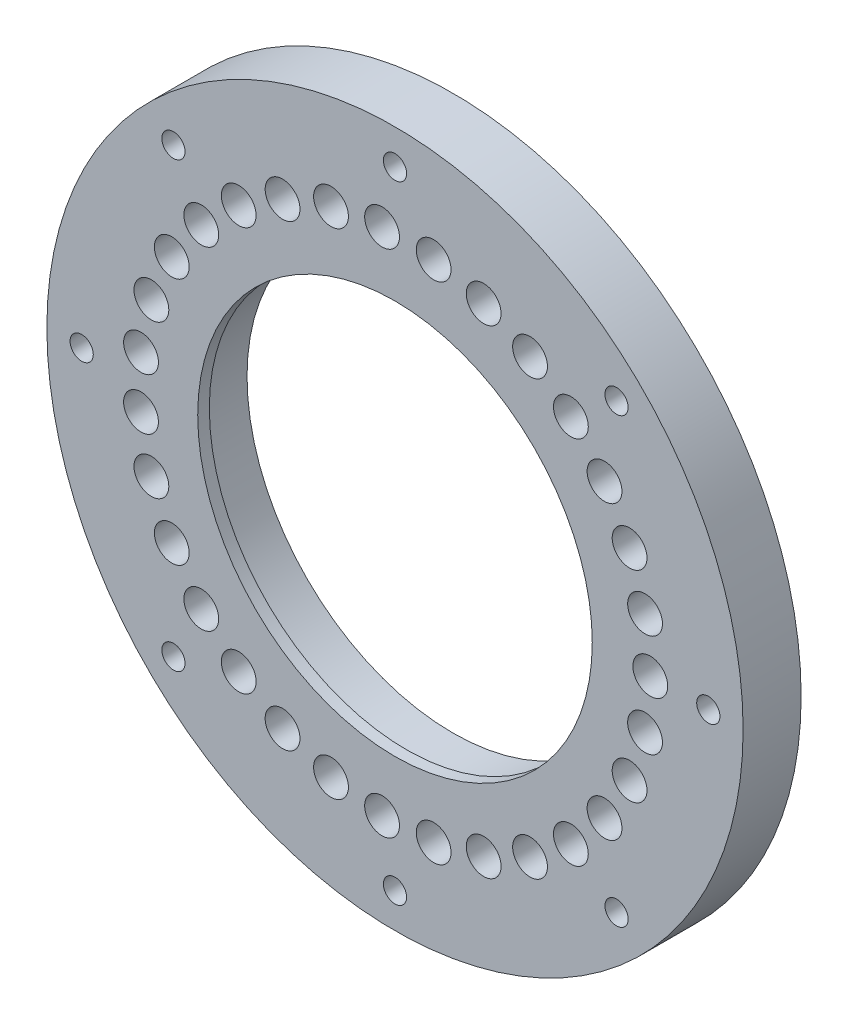
SolidWorks part; units mm, degrees
ref_plane "Front Plane" through (0, 0, 0) normal (0, 0, 1) x (1, 0, 0)
ref_plane "Top Plane" through (0, 0, 0) normal (0, 1, 0) x (1, 0, 0)
ref_plane "Right Plane" through (0, 0, 0) normal (1, 0, 0) x (0, 0, -1)
sketch "Sketch1" plane through (0, 0, 0) normal (0, 0, 1) x (1, 0, 0)
  circle A0 centre (44, 0) radius 3
  circle A1 centre (43.0993, -8.8571) radius 3
  circle A2 centre (40.4341, -17.3517) radius 3
  circle A3 centre (36.1136, -25.1358) radius 3
  circle A4 centre (30.3145, -31.8909) radius 3
  circle A5 centre (23.2744, -37.3403) radius 3
  circle A6 centre (15.2814, -41.2611) radius 3
  circle A7 centre (6.6628, -43.4926) radius 3
  circle A8 centre (-2.2286, -43.9435) radius 3
  circle A9 centre (-11.0287, -42.5954) radius 3
  circle A10 centre (-19.3773, -39.5034) radius 3
  circle A11 centre (-26.9327, -34.7941) radius 3
  circle A12 centre (-33.3854, -28.6604) radius 3
  circle A13 centre (-38.4713, -21.3533) radius 3
  circle A14 centre (-41.9821, -13.172) radius 3
  circle A15 centre (-43.7743, -4.4514) radius 3
  circle A16 centre (-43.7743, 4.4514) radius 3
  circle A17 centre (-41.9821, 13.172) radius 3
  circle A18 centre (-38.4713, 21.3533) radius 3
  circle A19 centre (-33.3854, 28.6604) radius 3
  circle A20 centre (-26.9327, 34.7941) radius 3
  circle A21 centre (-19.3773, 39.5034) radius 3
  circle A22 centre (-11.0287, 42.5954) radius 3
  circle A23 centre (-2.2286, 43.9435) radius 3
  circle A24 centre (6.6628, 43.4926) radius 3
  circle A25 centre (15.2814, 41.2611) radius 3
  circle A26 centre (23.2744, 37.3403) radius 3
  circle A27 centre (30.3145, 31.8909) radius 3
  circle A28 centre (36.1136, 25.1358) radius 3
  circle A29 centre (40.4341, 17.3517) radius 3
  circle A30 centre (43.0993, 8.8571) radius 3
  arc A31 (59.9303, 2.891) -> (59.9303, -2.891) centre (0, 0) ccw
  circle A32 centre (0, 0) radius 34
  arc A33 (59.9303, -2.891) -> (59.9303, 2.891) centre (60, 0) ccw
  point P65 (0, 0)
  point P81 (0, 0)
  dimension "D1" = 6
  dimension "D4" = 120
  dimension "D5" = 68
  dimension "D2" = 44
  dimension "D3" = 31
extrude "Boss-Extrude1" add sketch "Sketch1" along normal blind 5
sketch "Sketch2" plane through (0, 0, 0) normal (0, 0, -1) x (-1, 0, 0)
  circle A0 centre (0, 0) radius 60
  circle A1 centre (0, 0) radius 10
  dimension "D1" = 20
extrude "Boss-Extrude2" add sketch "Sketch2" along normal blind 5
sketch "Sketch3" plane through (0, 0, 5) normal (0, 0, 1) x (1, 0, 0)
  circle A0 centre (0, 54) radius 2
  circle A1 centre (38.1838, 38.1838) radius 2
  circle A2 centre (54, 0) radius 2
  circle A3 centre (38.1838, -38.1838) radius 2
  circle A4 centre (0, -54) radius 2
  circle A5 centre (-38.1838, -38.1838) radius 2
  circle A6 centre (-54, 0) radius 2
  circle A7 centre (-38.1838, 38.1838) radius 2
  point P12 (0, 0)
  dimension "D1" = 4
  dimension "D2" = 54
  dimension "D3" = 8
extrude "Cut-Extrude1" cut sketch "Sketch3" against normal blind 35
sketch "Sketch5" plane through (0, 0, -5) normal (0, 0, -1) x (-1, 0, 0)
  circle A0 centre (0, 0) radius 35.5
  dimension "D1" = 71
extrude "Cut-Extrude3" cut sketch "Sketch5" against normal up to surface (5 mm away) up to face at (-10, 0, 0)
ref_plane "Plane1" through (0, 0, 0) normal (0.2588, 0.9659, 0) x (0, 0, -1)
sketch "Sketch6" plane through (0, 0, 0) normal (0, 0, -1) x (-1, 0, 0)
  circle A0 centre (0, 0) radius 35.5
extrude "Cut-Extrude4" cut sketch "Sketch6" against normal blind 3
sketch "Sketch7" plane through (0, 0, -5) normal (0, 0, -1) x (-1, 0, 0)
  circle A0 centre (0, 0) radius 60
  circle A1 centre (0, 0) radius 93.5279
extrude "Cut-Extrude5" cut sketch "Sketch7" against normal blind 10
